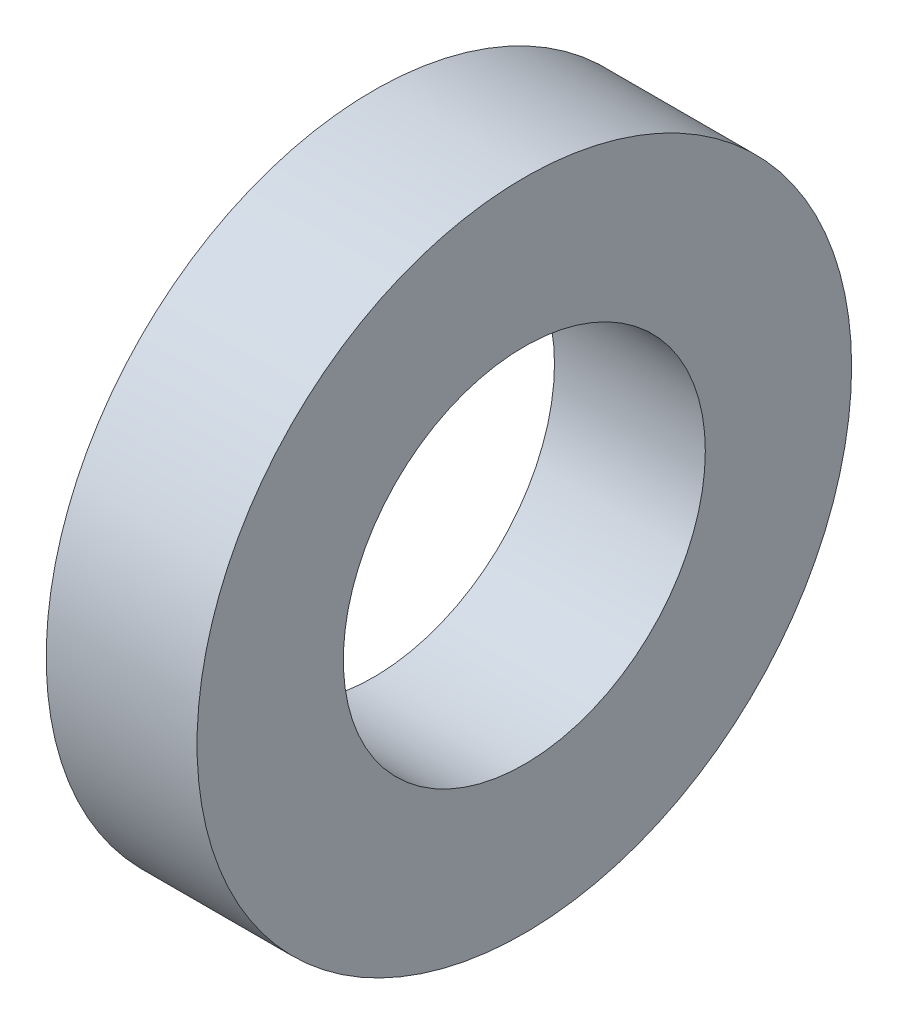
SolidWorks part; units mm, degrees
ref_plane "前视基准面" through (0, 0, 0) normal (0, 0, 1) x (1, 0, 0)
ref_plane "上视基准面" through (0, 0, 0) normal (0, 1, 0) x (1, 0, 0)
ref_plane "右视基准面" through (0, 0, 0) normal (1, 0, 0) x (0, 0, -1)
other "Configuration Table"
sketch "草图1" plane through (0, 0, 0) normal (1, 0, 0) x (0, 0, -1)
  circle A0 centre (0, 0) radius 6
  circle A1 centre (0, 0) radius 10.8495
  dimension "D1" = 12
extrude "凸台-拉伸1" add sketch "草图1" along normal blind 5
equation "\"w\"=10"
